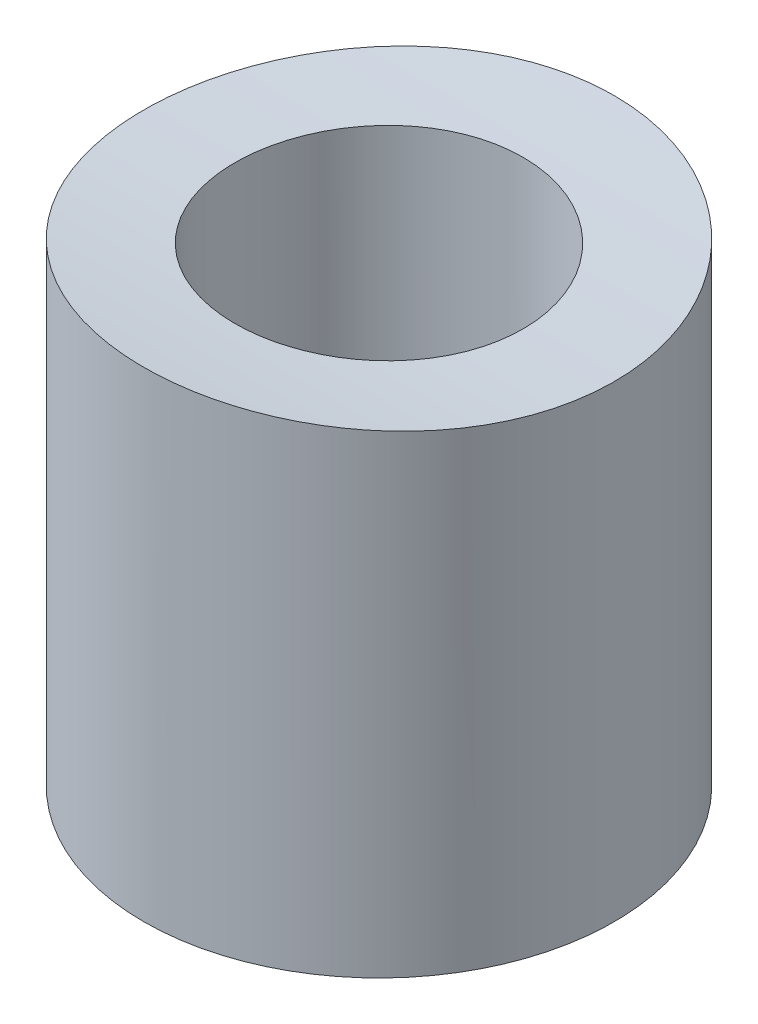
SolidWorks part; units mm, degrees
ref_plane "Front Plane" through (0, 0, 0) normal (0, 0, 1) x (1, 0, 0)
ref_plane "Top Plane" through (0, 0, 0) normal (0, 1, 0) x (1, 0, 0)
ref_plane "Right Plane" through (0, 0, 0) normal (1, 0, 0) x (0, 0, -1)
sketch "Sketch1" plane through (0, 0, 0) normal (0, 1, 0) x (1, 0, 0)
  circle A0 centre (0, 0) radius 24.5
  circle A1 centre (0, 0) radius 15
  dimension "D1" = 49
  dimension "D2" = 30
extrude "Boss-Extrude1" add sketch "Sketch1" along normal blind 50
sketch "Sketch2" plane through (0, 0, 0) normal (1, 0, 0) x (0, 0, -1)
  line L0 (15, 50) -> (-15, 50) construction
  line L1 (24.5, 50) -> (-24.5, 50)
  arc A0 (-24.5, 50) -> (24.5, 50) centre (0, 281.8089) ccw
  dimension "D1" = 466.2
extrude "Cut-Extrude1" cut sketch "Sketch2" against normal through all both and the other way through all
